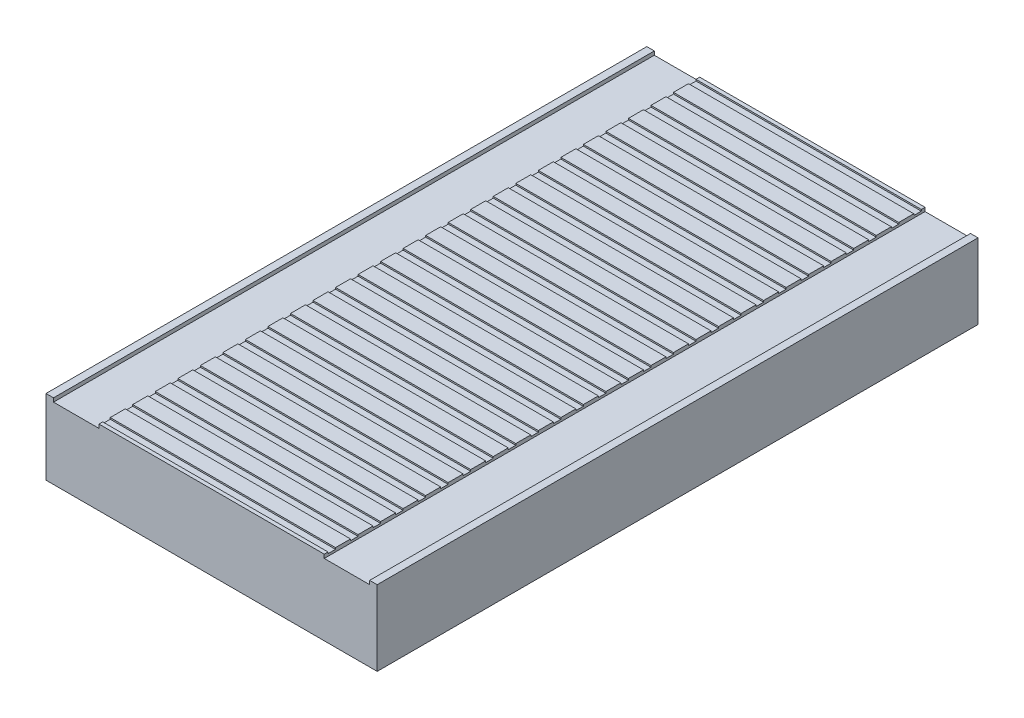
SolidWorks part; units mm, degrees
ref_plane "前视基准面" through (0, 0, 0) normal (0, 0, 1) x (1, 0, 0)
ref_plane "上视基准面" through (0, 0, 0) normal (0, 1, 0) x (1, 0, 0)
ref_plane "右视基准面" through (0, 0, 0) normal (1, 0, 0) x (0, 0, -1)
other "Configuration Table"
sketch "草图1" plane through (0, 0, 0) normal (0, 1, 0) x (1, 0, 0)
  line L1 (0, 0) -> (-441, 0)
  line L2 (0, 0) -> (0, 800)
  line L3 (0, 800) -> (-441, 800)
  line L4 (-441, 0) -> (-441, 800)
  dimension "D1" = 800
  dimension "D2" = 441
extrude "凸台-拉伸1" add sketch "草图1" along normal blind 95
sketch "草图3" plane through (0, 95, 0) normal (0, 1, 0) x (1, 0, 0)
  line L0 (-441, 0) -> (0, 0) construction
  line L1 (-441, 800) -> (-431, 800)
  line L2 (-441, 800) -> (-441, 0)
  line L3 (-441, 0) -> (-431, 0)
  line L4 (-431, 800) -> (-431, 0)
  line L5 (-220.5, 800) -> (-220.5, -52.8797) construction
  line L6 (0, 800) -> (-441, 800) construction
  line L7 (-70.5, 800) -> (-370.5, 800)
  line L8 (-370.5, 800) -> (-370.5, 0)
  line L9 (-370.5, 0) -> (-70.5, 0)
  line L10 (-70.5, 800) -> (-70.5, 0)
  line L11 (-10, 800) -> (-10, 0)
  line L12 (0, 0) -> (-10, 0)
  line L13 (0, 800) -> (0, 0)
  line L14 (0, 800) -> (-10, 800)
  point P15 (-220.5, 0)
  dimension "D1" = 10
  dimension "D2" = 150
extrude "凸台-拉伸2" add sketch "草图3" along normal blind 5
sketch "草图4" plane through (0, 100, 0) normal (0, 1, 0) x (1, 0, 0)
  line L0 (-370.5, 800) -> (-370.5, 0) construction
  line L1 (-370.5, 795) -> (-70.5, 795)
  line L2 (-370.5, 795) -> (-370.5, 785)
  line L3 (-370.5, 785) -> (-70.5, 785)
  line L4 (-70.5, 795) -> (-70.5, 785)
  line L5 (-70.5, 0) -> (-70.5, 800) construction
  line L6 (-70.5, 800) -> (-370.5, 800) construction
  line L7 (-370.5, 765) -> (-70.5, 765)
  line L8 (-370.5, 765) -> (-370.5, 755)
  line L9 (-370.5, 755) -> (-70.5, 755)
  line L10 (-70.5, 765) -> (-70.5, 755)
  line L11 (-370.5, 735) -> (-70.5, 735)
  line L12 (-370.5, 735) -> (-370.5, 725)
  line L13 (-370.5, 725) -> (-70.5, 725)
  line L14 (-70.5, 735) -> (-70.5, 725)
  line L15 (-370.5, 705) -> (-70.5, 705)
  line L16 (-370.5, 705) -> (-370.5, 695)
  line L17 (-370.5, 695) -> (-70.5, 695)
  line L18 (-70.5, 705) -> (-70.5, 695)
  line L19 (-370.5, 675) -> (-70.5, 675)
  line L20 (-370.5, 675) -> (-370.5, 665)
  line L21 (-370.5, 665) -> (-70.5, 665)
  line L22 (-70.5, 675) -> (-70.5, 665)
  line L23 (-370.5, 645) -> (-70.5, 645)
  line L24 (-370.5, 645) -> (-370.5, 635)
  line L25 (-370.5, 635) -> (-70.5, 635)
  line L26 (-70.5, 645) -> (-70.5, 635)
  line L27 (-370.5, 615) -> (-70.5, 615)
  line L28 (-370.5, 615) -> (-370.5, 605)
  line L29 (-370.5, 605) -> (-70.5, 605)
  line L30 (-70.5, 615) -> (-70.5, 605)
  line L31 (-370.5, 585) -> (-70.5, 585)
  line L32 (-370.5, 585) -> (-370.5, 575)
  line L33 (-370.5, 575) -> (-70.5, 575)
  line L34 (-70.5, 585) -> (-70.5, 575)
  line L35 (-370.5, 555) -> (-70.5, 555)
  line L36 (-370.5, 555) -> (-370.5, 545)
  line L37 (-370.5, 545) -> (-70.5, 545)
  line L38 (-70.5, 555) -> (-70.5, 545)
  line L39 (-370.5, 525) -> (-70.5, 525)
  line L40 (-370.5, 525) -> (-370.5, 515)
  line L41 (-370.5, 515) -> (-70.5, 515)
  line L42 (-70.5, 525) -> (-70.5, 515)
  line L43 (-370.5, 495) -> (-70.5, 495)
  line L44 (-370.5, 495) -> (-370.5, 485)
  line L45 (-370.5, 485) -> (-70.5, 485)
  line L46 (-70.5, 495) -> (-70.5, 485)
  line L47 (-370.5, 465) -> (-70.5, 465)
  line L48 (-370.5, 465) -> (-370.5, 455)
  line L49 (-370.5, 455) -> (-70.5, 455)
  line L50 (-70.5, 465) -> (-70.5, 455)
  line L51 (-370.5, 435) -> (-70.5, 435)
  line L52 (-370.5, 435) -> (-370.5, 425)
  line L53 (-370.5, 425) -> (-70.5, 425)
  line L54 (-70.5, 435) -> (-70.5, 425)
  line L55 (-370.5, 405) -> (-70.5, 405)
  line L56 (-370.5, 405) -> (-370.5, 395)
  line L57 (-370.5, 395) -> (-70.5, 395)
  line L58 (-70.5, 405) -> (-70.5, 395)
  line L59 (-370.5, 375) -> (-70.5, 375)
  line L60 (-370.5, 375) -> (-370.5, 365)
  line L61 (-370.5, 365) -> (-70.5, 365)
  line L62 (-70.5, 375) -> (-70.5, 365)
  line L63 (-370.5, 345) -> (-70.5, 345)
  line L64 (-370.5, 345) -> (-370.5, 335)
  line L65 (-370.5, 335) -> (-70.5, 335)
  line L66 (-70.5, 345) -> (-70.5, 335)
  line L67 (-370.5, 315) -> (-70.5, 315)
  line L68 (-370.5, 315) -> (-370.5, 305)
  line L69 (-370.5, 305) -> (-70.5, 305)
  line L70 (-70.5, 315) -> (-70.5, 305)
  line L71 (-370.5, 285) -> (-70.5, 285)
  line L72 (-370.5, 285) -> (-370.5, 275)
  line L73 (-370.5, 275) -> (-70.5, 275)
  line L74 (-70.5, 285) -> (-70.5, 275)
  line L75 (-370.5, 255) -> (-70.5, 255)
  line L76 (-370.5, 255) -> (-370.5, 245)
  line L77 (-370.5, 245) -> (-70.5, 245)
  line L78 (-70.5, 255) -> (-70.5, 245)
  line L79 (-370.5, 225) -> (-70.5, 225)
  line L80 (-370.5, 225) -> (-370.5, 215)
  line L81 (-370.5, 215) -> (-70.5, 215)
  line L82 (-70.5, 225) -> (-70.5, 215)
  line L83 (-370.5, 195) -> (-70.5, 195)
  line L84 (-370.5, 195) -> (-370.5, 185)
  line L85 (-370.5, 185) -> (-70.5, 185)
  line L86 (-70.5, 195) -> (-70.5, 185)
  line L87 (-370.5, 165) -> (-70.5, 165)
  line L88 (-370.5, 165) -> (-370.5, 155)
  line L89 (-370.5, 155) -> (-70.5, 155)
  line L90 (-70.5, 165) -> (-70.5, 155)
  line L91 (-370.5, 135) -> (-70.5, 135)
  line L92 (-370.5, 135) -> (-370.5, 125)
  line L93 (-370.5, 125) -> (-70.5, 125)
  line L94 (-70.5, 135) -> (-70.5, 125)
  line L95 (-370.5, 105) -> (-70.5, 105)
  line L96 (-370.5, 105) -> (-370.5, 95)
  line L97 (-370.5, 95) -> (-70.5, 95)
  line L98 (-70.5, 105) -> (-70.5, 95)
  line L99 (-370.5, 75) -> (-70.5, 75)
  line L100 (-370.5, 75) -> (-370.5, 65)
  line L101 (-370.5, 65) -> (-70.5, 65)
  line L102 (-70.5, 75) -> (-70.5, 65)
  line L103 (-370.5, 45) -> (-70.5, 45)
  line L104 (-370.5, 45) -> (-370.5, 35)
  line L105 (-370.5, 35) -> (-70.5, 35)
  line L106 (-70.5, 45) -> (-70.5, 35)
  line L107 (-370.5, 15) -> (-70.5, 15)
  line L108 (-370.5, 15) -> (-370.5, 5)
  line L109 (-370.5, 5) -> (-70.5, 5)
  line L110 (-70.5, 15) -> (-70.5, 5)
  dimension "D1" = 5
  dimension "D2" = 10
  dimension "D3" = 27
extrude "切除-拉伸1" cut sketch "草图4" against normal blind 2
